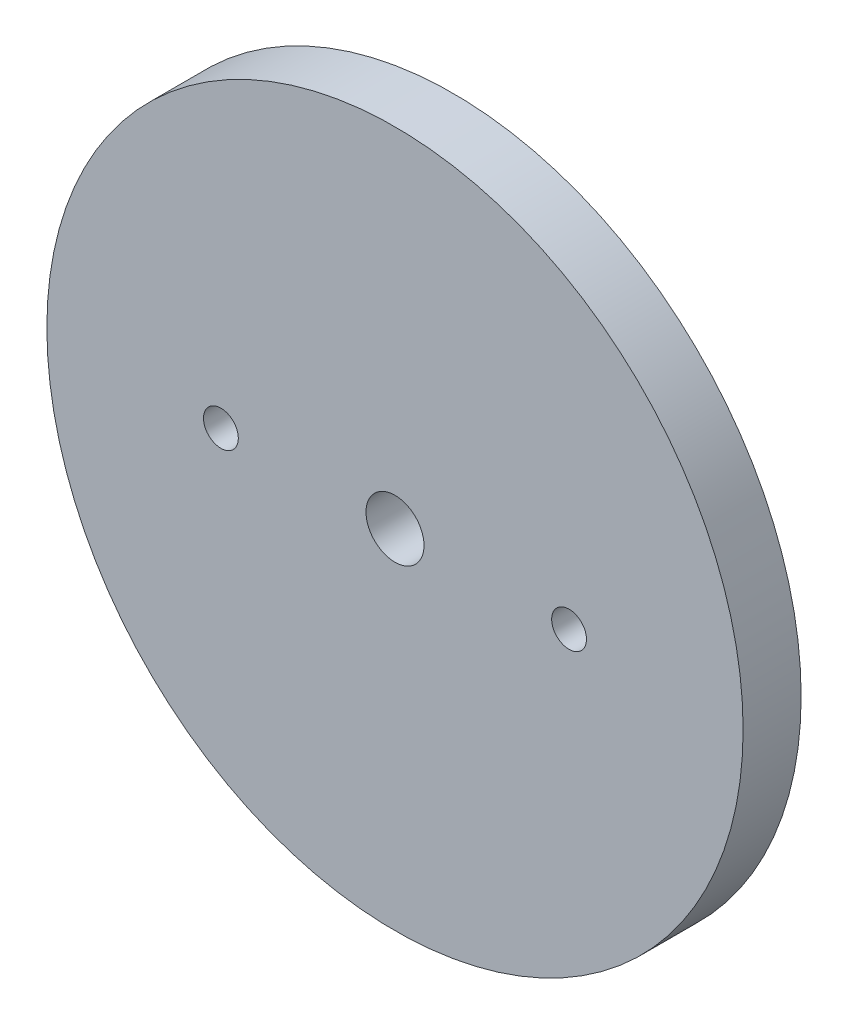
SolidWorks part; units mm, degrees
ref_plane "Front Plane" through (0, 0, 0) normal (0, 0, 1) x (1, 0, 0)
ref_plane "Top Plane" through (0, 0, 0) normal (0, 1, 0) x (1, 0, 0)
ref_plane "Right Plane" through (0, 0, 0) normal (1, 0, 0) x (0, 0, -1)
sketch "Sketch1" plane through (0, 0, 0) normal (0, 0, 1) x (1, 0, 0)
  circle A0 centre (0, 0) radius 60
extrude "Boss-Extrude1" add sketch "Sketch1" along normal blind 10
sketch "Sketch2" plane through (0, 0, 10) normal (0, 0, 1) x (1, 0, 0)
  circle A1 centre (0, 0) radius 5
extrude "Cut-Extrude1" cut sketch "Sketch2" against normal blind 10
sketch "Sketch3" plane through (0, 0, 10) normal (0, 0, 1) x (1, 0, 0)
  circle A0 centre (-30, 0) radius 3
  circle A1 centre (30, 0) radius 3
  dimension "D1" = 30
  dimension "D2" = 30
extrude "Cut-Extrude2" cut sketch "Sketch3" against normal blind 10
